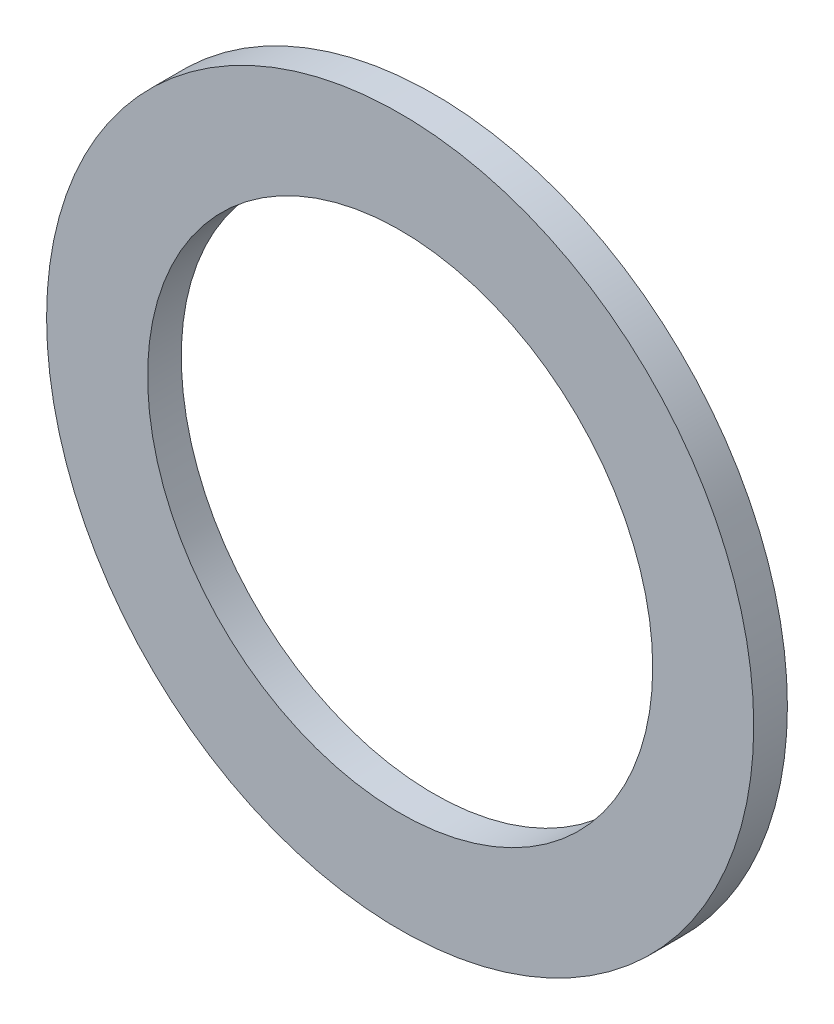
SolidWorks part; units mm, degrees
ref_plane "Front Plane" through (0, 0, 0) normal (0, 0, 1) x (1, 0, 0)
ref_plane "Top Plane" through (0, 0, 0) normal (0, 1, 0) x (1, 0, 0)
ref_plane "Right Plane" through (0, 0, 0) normal (1, 0, 0) x (0, 0, -1)
sketch "Sketch1" plane through (0, 0, 0) normal (0, 0, 1) x (1, 0, 0)
  circle A0 centre (0, 0) radius 7.5
  circle A1 centre (0, 0) radius 10.5
  dimension "D1" = 15
  dimension "D2" = 21
extrude "Boss-Extrude1" add sketch "Sketch1" along normal blind 1
